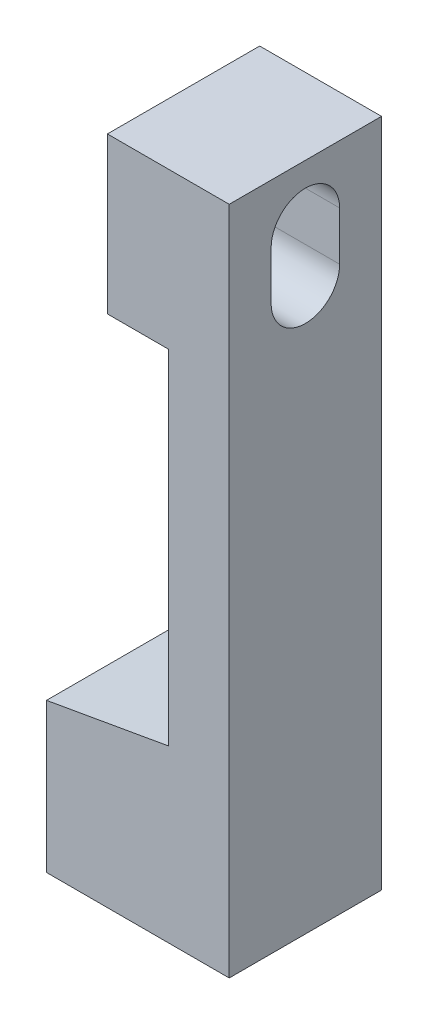
SolidWorks part; units mm, degrees
ref_plane "Front Plane" through (0, 0, 0) normal (0, 0, 1) x (1, 0, 0)
ref_plane "Top Plane" through (0, 0, 0) normal (0, 1, 0) x (1, 0, 0)
ref_plane "Right Plane" through (0, 0, 0) normal (1, 0, 0) x (0, 0, -1)
sketch "Sketch1" plane through (0, 0, 0) normal (1, 0, 0) x (0, 0, -1)
  line L1 (-7.9375, 34.925) -> (7.9375, 34.925)
  line L2 (-7.9375, 34.925) -> (-7.9375, -34.925)
  line L3 (-7.9375, -34.925) -> (7.9375, -34.925)
  line L4 (7.9375, 34.925) -> (7.9375, -34.925)
  line L5 (-7.9375, 34.925) -> (7.9375, -34.925) construction
  line L6 (-7.9375, -34.925) -> (7.9375, 34.925) construction
  point P0 (0, 0)
  dimension "D1" = 69.85
  dimension "D2" = 15.875
extrude "Boss-Extrude1" add sketch "Sketch1" along normal blind 6.35
sketch "Sketch2" plane through (0, 0, 0) normal (-1, 0, 0) x (0, 0, 1)
  line L0 (-7.9375, -34.925) -> (-7.9375, 34.925) construction
  line L1 (7.9375, 34.925) -> (-7.9375, 34.925)
  line L2 (7.9375, 34.925) -> (7.9375, 18.6742)
  line L4 (-7.9375, 34.925) -> (-7.9375, 15.875)
  line L5 (-7.9375, 15.875) -> (7.9375, 18.6742)
  line L6 (-7.9375, -34.925) -> (-7.9375, 34.925) construction
  dimension "D1" = 100
  dimension "D2" = 19.05
extrude "Boss-Extrude2" add sketch "Sketch2" along normal blind 6.35
sketch "Sketch3" plane through (0, 0, 0) normal (-1, 0, 0) x (0, 0, 1)
  line L0 (-7.9375, -34.925) -> (-7.9375, 15.875) construction
  line L1 (-7.9375, -19.9442) -> (-7.9375, -34.925)
  line L2 (-7.9375, -34.925) -> (7.9375, -34.925)
  line L3 (7.9375, -34.925) -> (7.9375, -17.145)
  line L4 (7.9375, 18.6742) -> (7.9375, -34.925) construction
  line L5 (7.9375, -17.145) -> (-7.9375, -19.9442)
  dimension "D1" = 100
  dimension "D2" = 17.78
extrude "Boss-Extrude3" add sketch "Sketch3" along normal blind 12.7
sketch "Sketch6" plane through (0, 0, -7.9375) normal (0, 0, -1) x (-1, 0, 0)
  line L0 (0, -17.145) -> (12.7, -17.145)
  line L1 (0, -19.9442) -> (0, 15.875) construction
  line L2 (12.7, -17.145) -> (12.7, -19.3844)
  line L3 (12.7, -19.3844) -> (0, -17.145)
  line L4 (12.7, -17.145) -> (0, -17.145) construction
  dimension "D1" = 10
extrude "Cut-Extrude1" cut sketch "Sketch6" against normal through all
sketch "Sketch7" plane through (6.35, 0, 0) normal (1, 0, 0) x (0, 0, -1)
  line L0 (0, 28.8417) -> (0, 23.7617) construction
  line L1 (3.5687, 28.8417) -> (3.5687, 23.7617)
  line L2 (-3.5687, 28.8417) -> (-3.5687, 23.7617)
  line L3 (7.9375, 15.875) -> (-7.9375, 18.6742) construction
  arc A0 (3.5687, 28.8417) -> (-3.5687, 28.8417) centre (0, 28.8417) ccw
  arc A1 (-3.5687, 23.7617) -> (3.5687, 23.7617) centre (0, 23.7617) ccw
  point P3 (0, 26.3017)
  dimension "D2" = 7.1374
  dimension "D1" = 8.89
  dimension "D3" = 5.08
extrude "Cut-Extrude2" cut sketch "Sketch7" against normal through all
hole_wizard "1/4 Clearance Hole1" positions "Sketch4" profile "Sketch5" hole size "1/4" standard "ANSI Inch"
sketch "Sketch4" plane through (6.35, 0, 0) normal (1, 0, 0) x (0, 0, -1)
  line L1 (7.9375, 15.875) -> (-7.9375, 18.6742) construction
  point P0 (0, 27.5913)
  dimension "D1" = 10.16
sketch "Sketch5" plane through (6.35, 27.5913, 0) normal (0, 1, 0) x (0, 0, -1)
  line L0 (0, 0) -> (0, 19.05)
  line L1 (0, 19.05) -> (3.5712, 19.05)
  line L2 (3.5712, 19.05) -> (3.5712, 0)
  line L5 (3.5712, 0) -> (0, 0)
  line L11 (0, -6.35) -> (0, 107.95) construction
  dimension "Thru Hole Dia." = 7.1425
  dimension "Thru Hole Depth" = 19.05
